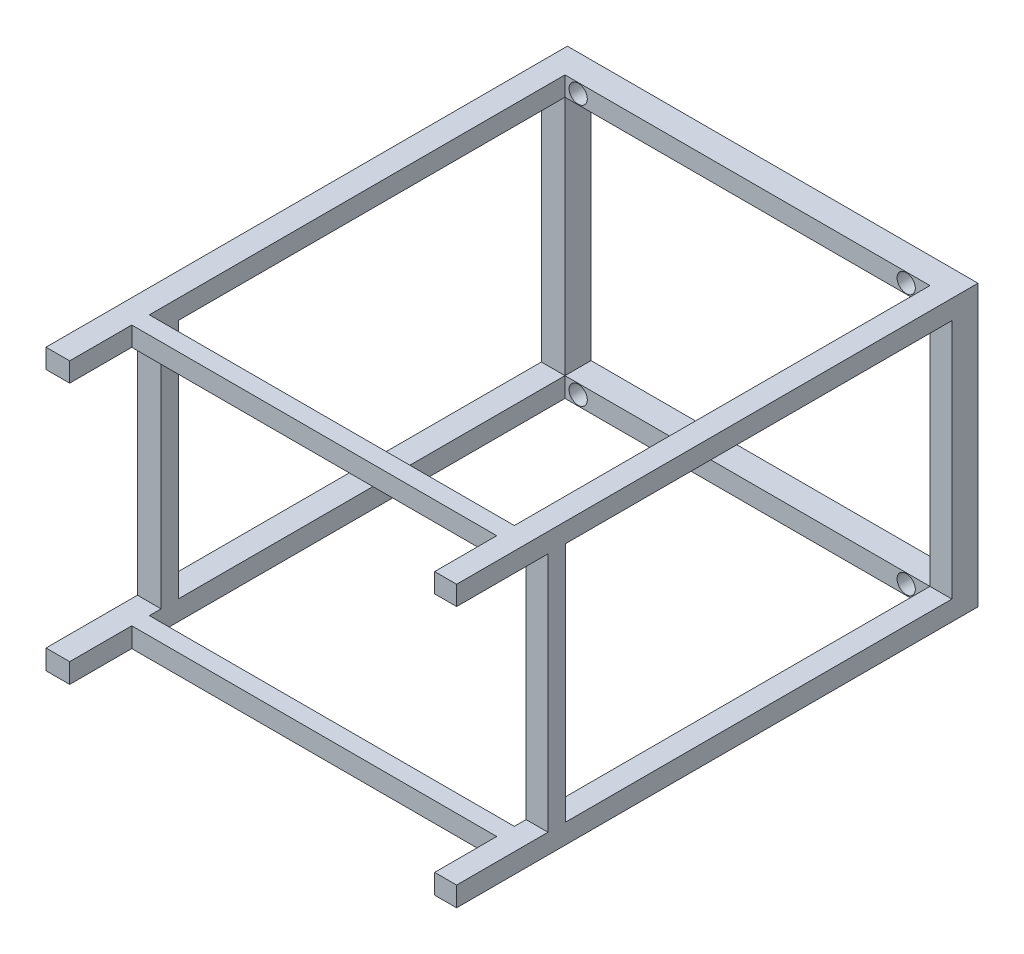
SolidWorks part; units mm, degrees
ref_plane "前视基准面" through (0, 0, 0) normal (0, 0, 1) x (1, 0, 0)
ref_plane "上视基准面" through (0, 0, 0) normal (0, 1, 0) x (1, 0, 0)
ref_plane "右视基准面" through (0, 0, 0) normal (1, 0, 0) x (0, 0, -1)
other "Configuration Table"
sketch "草图13" plane through (0, 0, 0) normal (0, 0, 1) x (1, 0, 0)
  line L1 (0, 0) -> (315, 0)
  line L2 (0, 0) -> (0, 215)
  line L3 (0, 215) -> (315, 215)
  line L4 (315, 0) -> (315, 215)
  line L5 (18.1516, 200.1571) -> (298.1516, 200.1571)
  line L6 (18.1516, 200.1571) -> (18.1516, 15.1571)
  line L7 (18.1516, 15.1571) -> (298.1516, 15.1571)
  line L8 (298.1516, 200.1571) -> (298.1516, 15.1571)
  line L9 (0, 215) -> (18.1516, 215)
  line L10 (0, 215) -> (0, 200.1571)
  line L11 (0, 200.1571) -> (18.1516, 200.1571)
  line L12 (18.1516, 215) -> (18.1516, 200.1571)
  line L13 (315, 215) -> (298.1516, 215)
  line L14 (315, 215) -> (315, 200.1571)
  line L15 (315, 200.1571) -> (298.1516, 200.1571)
  line L16 (298.1516, 215) -> (298.1516, 200.1571)
  line L17 (315, 0) -> (298.1516, 0)
  line L18 (315, 0) -> (315, 15.1571)
  line L19 (315, 15.1571) -> (298.1516, 15.1571)
  line L20 (298.1516, 0) -> (298.1516, 15.1571)
  line L21 (0, 0) -> (18.1516, 0)
  line L22 (0, 0) -> (0, 15.1571)
  line L23 (0, 15.1571) -> (18.1516, 15.1571)
  line L24 (18.1516, 0) -> (18.1516, 15.1571)
  dimension "D1" = 215
  dimension "D2" = 315
  dimension "D3" = 185
  dimension "D4" = 280
sketch "草图29" plane through (0, 0, 0) normal (0, 0, 1) x (1, 0, 0)
  line L1 (0, 0) -> (315, 0)
  line L2 (0, 0) -> (0, 215)
  line L3 (0, 215) -> (315, 215)
  line L4 (315, 0) -> (315, 215)
  line L5 (18.1516, 200.1571) -> (298.1516, 200.1571)
  line L6 (18.1516, 200.1571) -> (18.1516, 15.1571)
  line L7 (18.1516, 15.1571) -> (298.1516, 15.1571)
  line L8 (298.1516, 200.1571) -> (298.1516, 15.1571)
  line L9 (0, 215) -> (18.1516, 215)
  line L10 (0, 215) -> (0, 200.1571)
  line L11 (0, 200.1571) -> (18.1516, 200.1571)
  line L12 (18.1516, 215) -> (18.1516, 200.1571)
  line L13 (315, 215) -> (298.1516, 215)
  line L14 (315, 215) -> (315, 200.1571)
  line L15 (315, 200.1571) -> (298.1516, 200.1571)
  line L16 (298.1516, 215) -> (298.1516, 200.1571)
  line L17 (315, 0) -> (298.1516, 0)
  line L18 (315, 0) -> (315, 15.1571)
  line L19 (315, 15.1571) -> (298.1516, 15.1571)
  line L20 (298.1516, 0) -> (298.1516, 15.1571)
  line L21 (0, 0) -> (18.1516, 0)
  line L22 (0, 0) -> (0, 15.1571)
  line L23 (0, 15.1571) -> (18.1516, 15.1571)
  line L24 (18.1516, 0) -> (18.1516, 15.1571)
  dimension "D1" = 215
  dimension "D2" = 315
  dimension "D3" = 185
  dimension "D4" = 280
extrude "凸台-拉伸14" add sketch "草图13" along normal blind 20 contours L16 L3 L12 L5 | L2 L23 L6 L11 | L24 L1 L20 L7 | L19 L4 L15 L8
extrude "凸台-拉伸15" add sketch "草图29" along normal blind 400 contours L12 L3 L2 L11 | L3 L16 L15 L4 | L1 L24 L23 L2 | L20 L1 L4 L19
sketch "草图30" plane through (0, 0, 0) normal (0, -1, 0) x (1, 0, 0)
  line L0 (18.1516, 400) -> (18.1516, 20) construction
  line L1 (18.1516, 352.3602) -> (298.1516, 352.3602)
  line L2 (18.1516, 352.3602) -> (18.1516, 338.8602)
  line L3 (18.1516, 338.8602) -> (298.1516, 338.8602)
  line L4 (298.1516, 352.3602) -> (298.1516, 338.8602)
  line L5 (298.1516, 400) -> (298.1516, 20) construction
  dimension "D1" = 13.5
sketch "草图31" plane through (0, 215, 0) normal (0, 1, 0) x (1, 0, 0)
  line L1 (18.1516, -338.8602) -> (298.1516, -338.8602)
  line L2 (18.1516, -338.8602) -> (18.1516, -352.3602)
  line L3 (18.1516, -352.3602) -> (298.1516, -352.3602)
  line L4 (298.1516, -338.8602) -> (298.1516, -352.3602)
sketch "草图32" plane through (0, 0, 0) normal (-1, 0, 0) x (0, 0, 1)
  line L0 (338.8602, 215) -> (338.8602, 0) construction
  line L1 (338.8602, 215) -> (352.3602, 215) construction
  line L2 (352.3602, 0) -> (338.8602, 0) construction
  line L3 (329.865, 215) -> (329.865, 0) construction
  line L6 (400, 215) -> (0, 215) construction
  line L7 (400, 0) -> (0, 0) construction
  line L8 (400, 200.1571) -> (20, 200.1571) construction
  line L9 (316.365, 200.1571) -> (329.865, 200.1571)
  line L10 (316.365, 200.1571) -> (316.365, 15.1571)
  line L11 (316.365, 15.1571) -> (329.865, 15.1571)
  line L12 (329.865, 200.1571) -> (329.865, 15.1571)
  line L13 (400, 15.1571) -> (20, 15.1571) construction
  dimension "D1" = 13.5
sketch "草图33" plane through (315, 0, 0) normal (1, 0, 0) x (0, 0, -1)
  line L1 (-329.865, 200.1571) -> (-316.365, 200.1571)
  line L2 (-329.865, 200.1571) -> (-329.865, 15.1571)
  line L3 (-329.865, 15.1571) -> (-316.365, 15.1571)
  line L4 (-316.365, 200.1571) -> (-316.365, 15.1571)
extrude "凸台-拉伸16" add sketch "草图33" against normal up to vertex
extrude "凸台-拉伸17" add sketch "草图32" against normal up to vertex
extrude "凸台-拉伸18" add sketch "草图31" against normal up to vertex
extrude "凸台-拉伸19" add sketch "草图30" against normal up to vertex (15.1571 mm away) up to point (298.1515, 15.1571, 20)
sketch "草图34" plane through (0, 0, 0) normal (0, 0, -1) x (-1, 0, 0)
  line L0 (-279.91, 215) -> (-279.91, 200.1571) construction
  line L3 (-315, 0) -> (-315, 215) construction
  line L4 (-28.27, 215) -> (-28.27, 200.1571) construction
  line L5 (0, 0) -> (0, 215) construction
  circle A0 centre (-279.91, 207.5785) radius 7
  circle A1 centre (-28.27, 207.5785) radius 7
  circle A3 centre (-28.27, 7.5668) radius 7
  circle A4 centre (-279.91, 7.5668) radius 7
  dimension "D2" = 28.27
  dimension "D1" = 35.09
extrude "切除-拉伸1" cut sketch "草图34" against normal up to surface (20 mm away) contours A0 | A4 | A1 | A3 up to face at (158.1516, 7.5785, 20)
